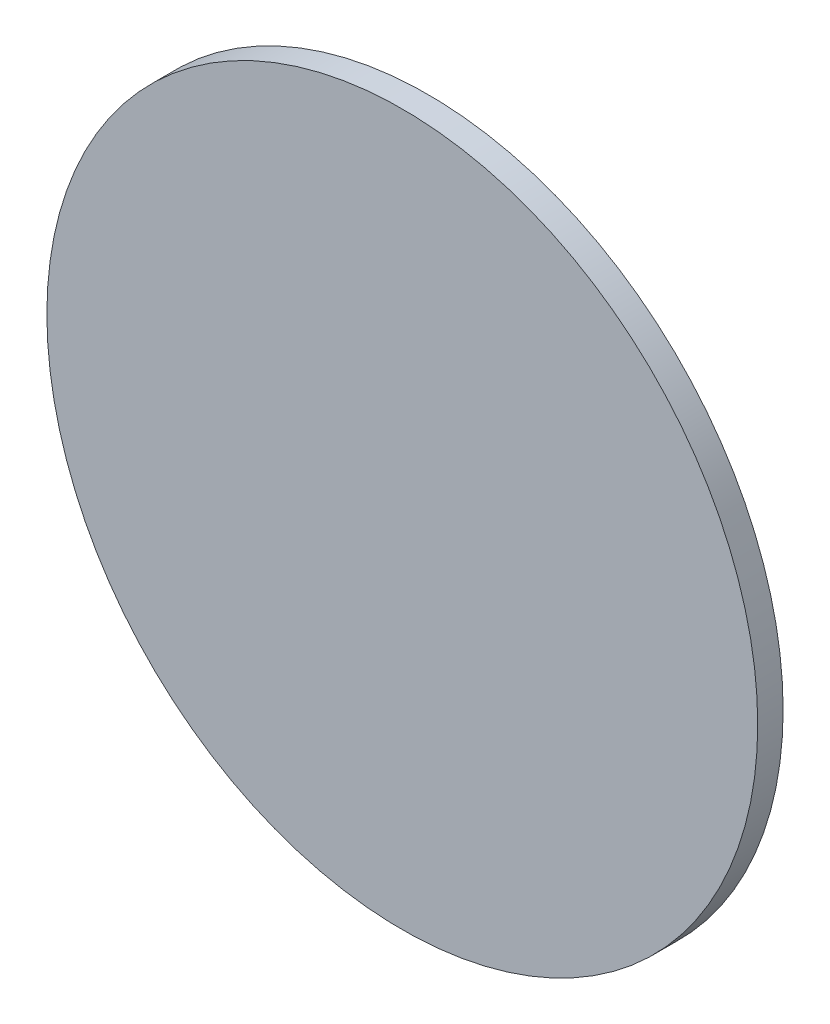
SolidWorks part; units mm, degrees
ref_plane "Front Plane" through (0, 0, 0) normal (0, 0, 1) x (1, 0, 0)
ref_plane "Top Plane" through (0, 0, 0) normal (0, 1, 0) x (1, 0, 0)
ref_plane "Right Plane" through (0, 0, 0) normal (1, 0, 0) x (0, 0, -1)
sketch "Sketch1" plane through (0, 0, 0) normal (0, 0, 1) x (1, 0, 0)
  circle A0 centre (0, 0) radius 140
  dimension "D1" = 280
extrude "Boss-Extrude1" add sketch "Sketch1" along normal blind 10
sketch "SketchText" plane through (0, 0, 0) normal (0, 0, -1) x (-1, 0, 0)
  line L0 (-1.2335, 30.9741) -> (23.9188, 30.9741) construction
  line L1 (-5.2335, 31.9741) -> (-2.2335, 31.9741)
  line L2 (-5.2335, 31.9741) -> (-5.2335, 34.9741)
  line L3 (-5.2335, 34.9741) -> (-2.2335, 34.9741)
  line L4 (-2.2335, 31.9741) -> (-2.2335, 34.9741)
  line L5 (-5.2335, 31.9741) -> (-2.2335, 34.9741) construction
  line L6 (-5.2335, 34.9741) -> (-2.2335, 31.9741) construction
  line L7 (-6.2335, 30.9741) -> (-1.2335, 30.9741)
  line L8 (-6.2335, 30.9741) -> (-6.2335, 35.9741)
  line L9 (-6.2335, 35.9741) -> (-1.2335, 35.9741)
  line L10 (-1.2335, 30.9741) -> (-1.2335, 35.9741)
  line L11 (-6.2335, 30.9741) -> (-1.2335, 35.9741) construction
  line L12 (-6.2335, 35.9741) -> (-1.2335, 30.9741) construction
  text T0 " Test Text"
  point P0 (-3.7335, 33.4741)
  point P5 (-3.7335, 33.4741)
  point P12 (-15.3918, 47.5639)
  point P13 (23.9188, 30.9741)
  dimension "D1" = 5
  dimension "D2" = 3
  dimension "D3" = 5
  dimension "D4" = 3
extrude "Cut-Extrude1" cut sketch "SketchText" against normal blind 0.5
